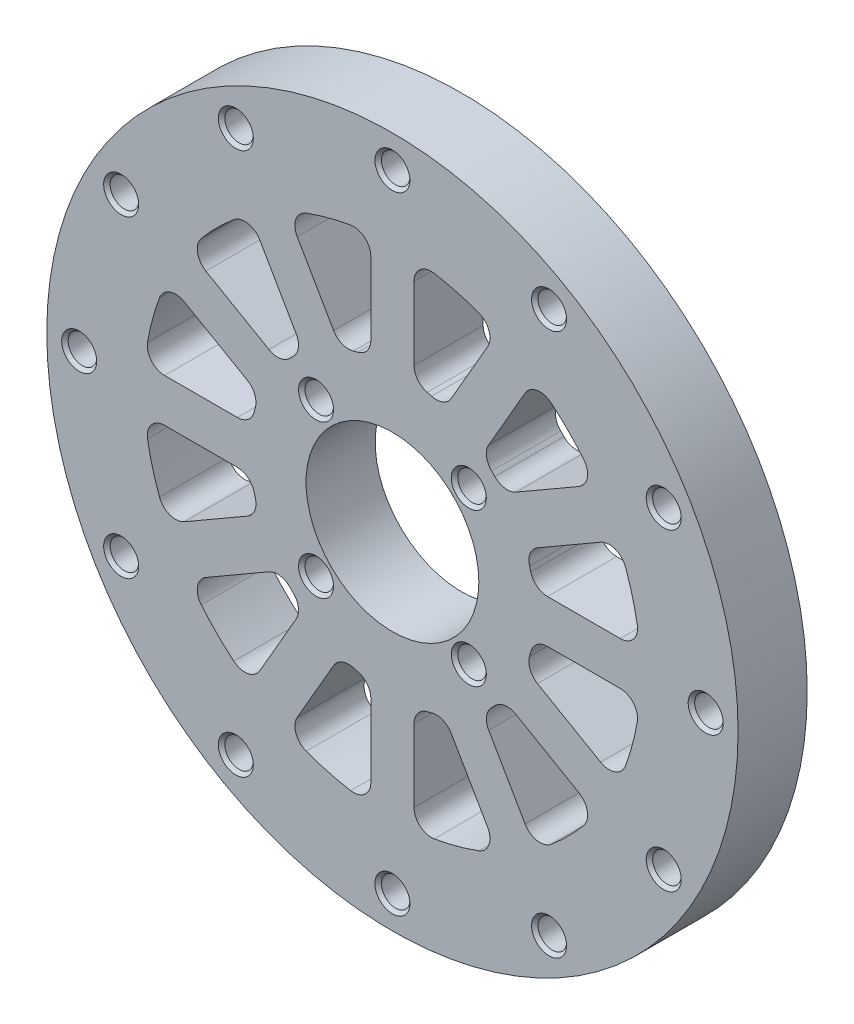
SolidWorks part; units mm, degrees
ref_plane "Front Plane" through (0, 0, 0) normal (0, 0, 1) x (1, 0, 0)
ref_plane "Top Plane" through (0, 0, 0) normal (0, 1, 0) x (1, 0, 0)
ref_plane "Right Plane" through (0, 0, 0) normal (1, 0, 0) x (0, 0, -1)
sketch "Sketch1" plane through (0, 0, 0) normal (0, 0, 1) x (1, 0, 0)
  line L0 (-28.75, 0) -> (28.75, 0) construction
  line L1 (0, 28.75) -> (0, -28.75) construction
  line L2 (0, 0) -> (8.8388, 8.8388) construction
  line L3 (0, 0) -> (-8.8388, -8.8388) construction
  line L4 (0, 0) -> (-8.8388, 8.8388) construction
  line L5 (0, 0) -> (8.8388, -8.8388) construction
  line L6 (-2.5, 28.6411) -> (-2.5, 16.3095)
  line L7 (2.5, 28.6411) -> (2.5, 16.3095)
  line L8 (12.1555, 26.0539) -> (5.9897, 15.3744)
  line L9 (16.4856, 23.5539) -> (10.3198, 12.8744)
  line L10 (23.5539, 16.4856) -> (12.8744, 10.3198)
  line L11 (26.0539, 12.1555) -> (15.3744, 5.9897)
  line L12 (28.6411, 2.5) -> (16.3095, 2.5)
  line L13 (28.6411, -2.5) -> (16.3095, -2.5)
  line L14 (26.0539, -12.1555) -> (15.3744, -5.9897)
  line L15 (23.5539, -16.4856) -> (12.8744, -10.3198)
  line L16 (16.4856, -23.5539) -> (10.3198, -12.8744)
  line L17 (12.1555, -26.0539) -> (5.9897, -15.3744)
  line L18 (2.5, -28.6411) -> (2.5, -16.3095)
  line L19 (-2.5, -28.6411) -> (-2.5, -16.3095)
  line L20 (-12.1555, -26.0539) -> (-5.9897, -15.3744)
  line L21 (-16.4856, -23.5539) -> (-10.3198, -12.8744)
  line L22 (-23.5539, -16.4856) -> (-12.8744, -10.3198)
  line L23 (-26.0539, -12.1555) -> (-15.3744, -5.9897)
  line L24 (-28.6411, -2.5) -> (-16.3095, -2.5)
  line L25 (-28.6411, 2.5) -> (-16.3095, 2.5)
  line L26 (-26.0539, 12.1555) -> (-15.3744, 5.9897)
  line L27 (-23.5539, 16.4856) -> (-12.8744, 10.3198)
  line L28 (-16.4856, 23.5539) -> (-10.3198, 12.8744)
  line L29 (-12.1555, 26.0539) -> (-5.9897, 15.3744)
  line L30 (0, 0) -> (2.5, 16.3095) construction
  line L31 (0, 28.75) -> (0, 40) construction
  circle A0 centre (0, 0) radius 40
  arc A1 (-16.4856, 23.5539) -> (-23.5539, 16.4856) centre (0, 0) ccw
  arc A2 (-10.3198, 12.8744) -> (-12.8744, 10.3198) centre (0, 0) ccw
  circle A3 centre (0, 0) radius 12.5 construction
  circle A4 centre (0, 0) radius 10
  arc A5 (-15.3744, 5.9897) -> (-16.3095, 2.5) centre (0, 0) ccw
  arc A6 (-16.3095, -2.5) -> (-15.3744, -5.9897) centre (0, 0) ccw
  arc A7 (-12.8744, -10.3198) -> (-10.3198, -12.8744) centre (0, 0) ccw
  arc A8 (-5.9897, -15.3744) -> (-2.5, -16.3095) centre (0, 0) ccw
  arc A9 (2.5, -16.3095) -> (5.9897, -15.3744) centre (0, 0) ccw
  arc A10 (10.3198, -12.8744) -> (12.8744, -10.3198) centre (0, 0) ccw
  arc A11 (15.3744, -5.9897) -> (16.3095, -2.5) centre (0, 0) ccw
  arc A12 (16.3095, 2.5) -> (15.3744, 5.9897) centre (0, 0) ccw
  arc A13 (12.8744, 10.3198) -> (10.3198, 12.8744) centre (0, 0) ccw
  arc A14 (5.9897, 15.3744) -> (2.5, 16.3095) centre (0, 0) ccw
  arc A15 (-2.5, 16.3095) -> (-5.9897, 15.3744) centre (0, 0) ccw
  circle A16 centre (0, 0) radius 28.75 construction
  arc A17 (-26.0539, 12.1555) -> (-28.6411, 2.5) centre (0, 0) ccw
  arc A18 (-28.6411, -2.5) -> (-26.0539, -12.1555) centre (0, 0) ccw
  arc A19 (-23.5539, -16.4856) -> (-16.4856, -23.5539) centre (0, 0) ccw
  arc A20 (-12.1555, -26.0539) -> (-2.5, -28.6411) centre (0, 0) ccw
  arc A21 (2.5, -28.6411) -> (12.1555, -26.0539) centre (0, 0) ccw
  arc A22 (16.4856, -23.5539) -> (23.5539, -16.4856) centre (0, 0) ccw
  arc A23 (26.0539, -12.1555) -> (28.6411, -2.5) centre (0, 0) ccw
  arc A24 (28.6411, 2.5) -> (26.0539, 12.1555) centre (0, 0) ccw
  arc A25 (23.5539, 16.4856) -> (16.4856, 23.5539) centre (0, 0) ccw
  arc A26 (12.1555, 26.0539) -> (2.5, 28.6411) centre (0, 0) ccw
  arc A27 (-2.5, 28.6411) -> (-12.1555, 26.0539) centre (0, 0) ccw
  circle A28 centre (0, 0) radius 34.375 construction
  circle A29 centre (0, 0) radius 16.5 construction
  point P65 (0, 34.375)
  dimension "D1" = 80
  dimension "D3" = 33
  dimension "D4" = 25
  dimension "D5" = 20
  dimension "D2" = 57.5
  dimension "D7" = 12
  dimension "D6" = 45
  dimension "D8" = 5
extrude "Boss-Extrude1" add sketch "Sketch1" along normal mid plane 8 contours A25 L9 A13 L10
hole_wizard "M4x0.7 Tapped Hole2" positions "Sketch5" profile "Sketch6" tap size "M4x0.7" standard "ANSI Metric" end condition through all
sketch "Sketch5" plane through (0, 0, 4) normal (0, 0, 1) x (1, 0, 0)
  point P0 (-8.8388, 8.8388)
  point P3 (-8.8388, -8.8388)
  point P6 (8.8388, -8.8388)
  point P9 (8.8388, 8.8388)
sketch "Sketch6" plane through (-8.8388, 8.8388, 4) normal (1, 0, 0) x (0, -1, 0)
  line L0 (0, 0) -> (0, 8)
  line L1 (0, 8) -> (1.65, 8)
  line L2 (1.65, 8) -> (1.65, 0.375)
  line L3 (1.65, 0.375) -> (2.025, 0)
  line L5 (2.025, 0) -> (0, 0)
  line L6 (-1.65, 0.375) -> (-2.025, 0) construction
  line L11 (0, -6.35) -> (0, 107.95) construction
  dimension "Thru Tap Drill Dia." = 3.3
  dimension "Thru Tap Drill Depth" = 8
  dimension "Near C'Sink Dia." = 4.05
  dimension "Near C'Sink Angle" = 90
cosmetic thread "Hole Thread2" parameters "D2"=4
cosmetic thread "Hole Thread3" parameters "D2"=4
cosmetic thread "Hole Thread4" parameters "D2"=4
cosmetic thread "Hole Thread5" parameters "D2"=4
hole_wizard "M4x0.7 Tapped Hole3" positions "Sketch9" profile "Sketch10" tap size "M4x0.7" standard "ANSI Metric" end condition through all
sketch "Sketch9" plane through (0, 0, 4) normal (0, 0, 1) x (1, 0, 0)
  line L0 (0, 0) -> (0, 36.25) construction
  circle A0 centre (0, 0) radius 36.25 construction
  point P0 (0, 36.25)
  dimension "D1" = 72.5
sketch "Sketch10" plane through (0, 36.25, 4) normal (1, 0, 0) x (0, -1, 0)
  line L0 (0, 0) -> (0, 8)
  line L1 (0, 8) -> (1.65, 8)
  line L2 (1.65, 8) -> (1.65, 0.375)
  line L3 (1.65, 0.375) -> (2.025, 0)
  line L5 (2.025, 0) -> (0, 0)
  line L6 (-1.65, 0.375) -> (-2.025, 0) construction
  line L11 (0, -6.35) -> (0, 107.95) construction
  dimension "Thru Tap Drill Dia." = 3.3
  dimension "Thru Tap Drill Depth" = 8
  dimension "Near C'Sink Dia." = 4.05
  dimension "Near C'Sink Angle" = 90
cosmetic thread "Hole Thread6" parameters "D2"=4
sketch "Sketch11" plane through (0, 0, 0) normal (1, 0, 0) x (0, 0, -1)
  line L0 (0, 0) -> (-4, 0) construction
  line L1 (0, 34.375) -> (0, -34.375) construction
  line L2 (-4, 40) -> (-4, -40) construction
pattern_circular "CirPattern1" count 12 every 30 about axis through (0, 0, 0) along (0, 0, 1) of "M4x0.7 Tapped Hole3"
cosmetic thread "Hole Thread7" parameters "D2"=4
cosmetic thread "Hole Thread8" parameters "D2"=4
cosmetic thread "Hole Thread9" parameters "D2"=4
cosmetic thread "Hole Thread10" parameters "D2"=4
cosmetic thread "Hole Thread11" parameters "D2"=4
cosmetic thread "Hole Thread12" parameters "D2"=4
cosmetic thread "Hole Thread13" parameters "D2"=4
cosmetic thread "Hole Thread14" parameters "D2"=4
cosmetic thread "Hole Thread15" parameters "D2"=4
cosmetic thread "Hole Thread16" parameters "D2"=4
cosmetic thread "Hole Thread17" parameters "D2"=4
fillet "Fillet1" radius 2 48 edges at (-16.3095, 2.5, 0) (-15.3744, 5.9897, 0) (-26.0539, 12.1555, 0) (-28.6411, 2.5, 0) (-16.3095, -2.5, 0) (-15.3744, -5.9897, 0) (-28.6411, -2.5, 0) (-26.0539, -12.1555, 0) (-10.3198, -12.8744, 0) (-12.8744, -10.3198, 0) (-16.4856, -23.5539, 0) (-23.5539, -16.4856, 0) (-2.5, -28.6411, 0) (-2.5, -16.3095, 0) (-5.9897, -15.3744, 0) (-12.1555, -26.0539, 0) (12.1555, -26.0539, 0) (2.5, -28.6411, 0) (5.9897, -15.3744, 0) (2.5, -16.3095, 0) (16.4856, -23.5539, 0) (23.5539, -16.4856, 0) (12.8744, -10.3198, 0) (10.3198, -12.8744, 0) (28.6411, -2.5, 0) (26.0539, -12.1555, 0) (16.3095, -2.5, 0) (15.3744, -5.9897, 0) (28.6411, 2.5, 0) (26.0539, 12.1555, 0) (16.3095, 2.5, 0) (15.3744, 5.9897, 0) (23.5539, 16.4856, 0) (16.4856, 23.5539, 0) (10.3198, 12.8744, 0) (12.8744, 10.3198, 0) (5.9897, 15.3744, 0) (2.5, 16.3095, 0) (12.1555, 26.0539, 0) (2.5, 28.6411, 0) (-2.5, 16.3095, 0) (-5.9897, 15.3744, 0) (-12.8744, 10.3198, 0) (-10.3198, 12.8744, 0) (-2.5, 28.6411, 0) (-12.1555, 26.0539, 0) (-16.4856, 23.5539, 0) (-23.5539, 16.4856, 0)
